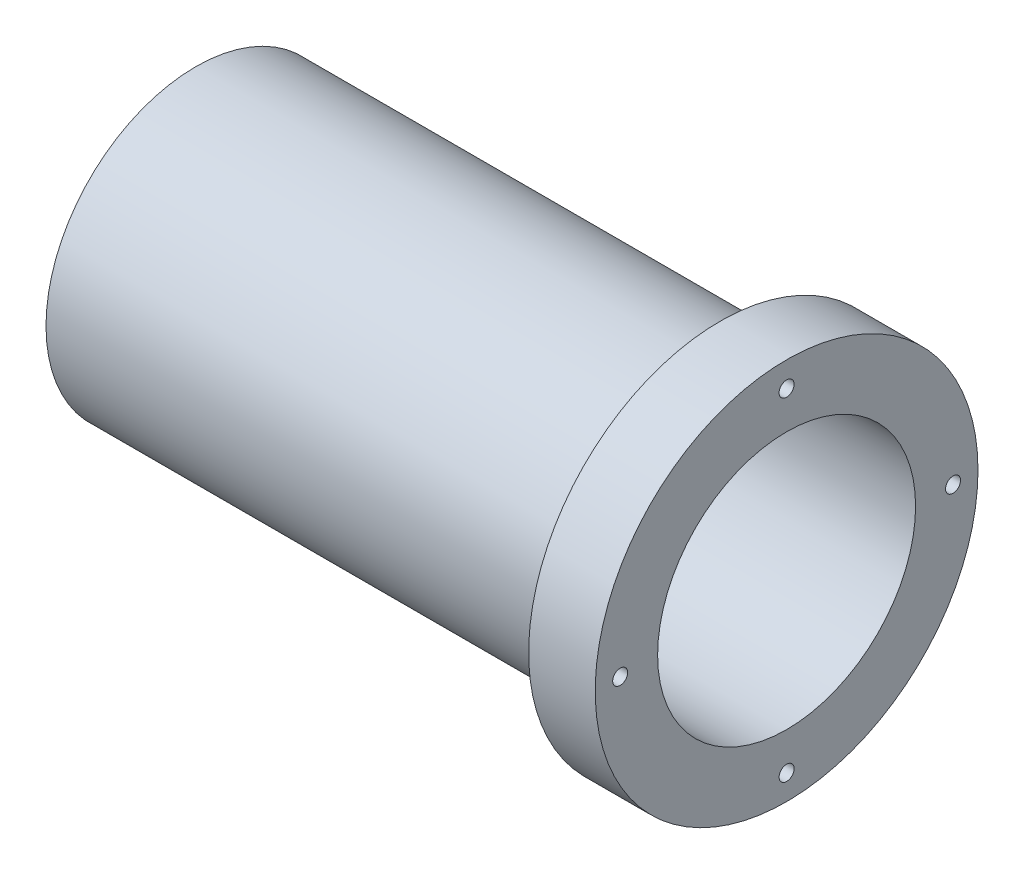
SolidWorks part; units mm, degrees
ref_plane "前视基准面" through (0, 0, 0) normal (0, 0, 1) x (1, 0, 0)
ref_plane "上视基准面" through (0, 0, 0) normal (0, 1, 0) x (1, 0, 0)
ref_plane "右视基准面" through (0, 0, 0) normal (1, 0, 0) x (0, 0, -1)
sketch "草图1" plane through (0, 0, 0) normal (1, 0, 0) x (0, 0, -1)
  circle A0 centre (0, 0) radius 31
  circle A1 centre (0, 0) radius 36
extrude "凸台-拉伸1" add sketch "草图1" along normal blind 121
sketch "草图2" plane through (121, 0, 0) normal (1, 0, 0) x (0, 0, -1)
  circle A0 centre (0, 0) radius 31
  circle A1 centre (0, 0) radius 46
extrude "凸台-拉伸2" add sketch "草图2" along normal blind 16
sketch "草图3" plane through (0, 0, 0) normal (-1, 0, 0) x (0, 0, 1)
  circle A0 centre (0, 0) radius 36
  circle A1 centre (0, 0) radius 28.5
extrude "凸台-拉伸3" add sketch "草图3" along normal blind 2
sketch "草图4" plane through (-2, 0, 0) normal (-1, 0, 0) x (0, 0, 1)
  circle A0 centre (0, 0) radius 36
  circle A1 centre (0, 0) radius 17
extrude "凸台-拉伸4" add sketch "草图4" along normal blind 3
sketch "草图5" plane through (137, 0, 0) normal (1, 0, 0) x (0, 0, -1)
  line L0 (-71.6464, 0) -> (59.2324, 0) construction
  line L2 (0, 48.9022) -> (0, -50.4096) construction
  circle A4 centre (0, 40) radius 1.8
  circle A5 centre (40, 0) radius 1.8
  circle A6 centre (0, -40) radius 1.8
  circle A7 centre (-40, 0) radius 1.8
  point P17 (0, 0)
  dimension "D1" = 4
  dimension "D2" = 40
extrude "切除-拉伸1" cut sketch "草图5" against normal blind 20
